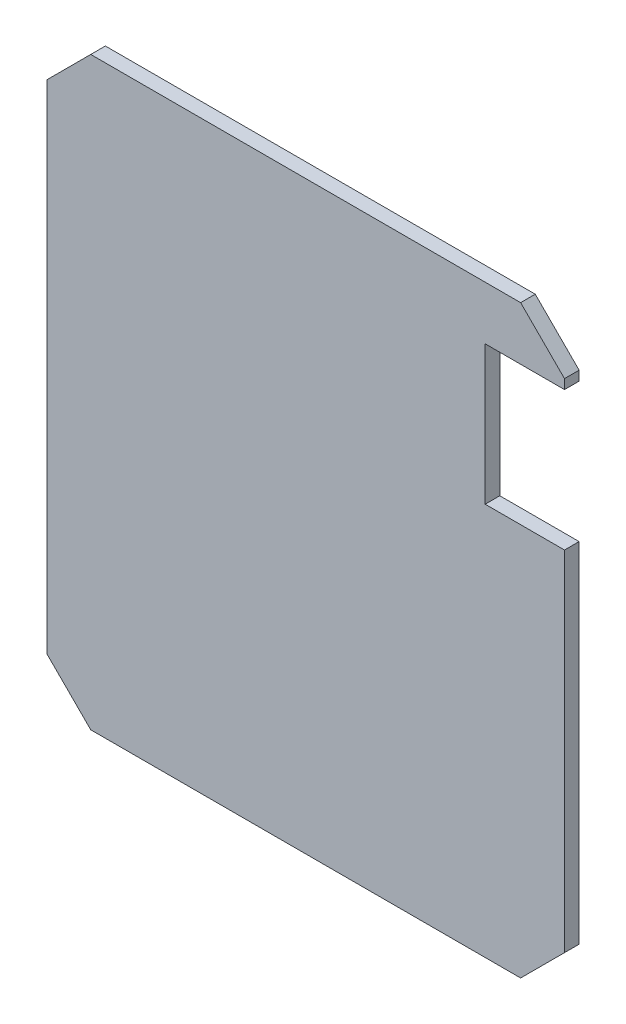
SolidWorks part; units mm, degrees
ref_plane "Front Plane" through (0, 0, 0) normal (0, 0, 1) x (1, 0, 0)
ref_plane "Top Plane" through (0, 0, 0) normal (0, 1, 0) x (1, 0, 0)
ref_plane "Right Plane" through (0, 0, 0) normal (1, 0, 0) x (0, 0, -1)
sketch "Sketch3" plane through (0, 0, 0) normal (0, 0, 1) x (1, 0, 0)
  line L0 (-17.75, 17) -> (-17.75, -17) construction
  line L1 (-14.7, 20) -> (14.7, 20)
  line L2 (-17.7, 17) -> (-17.7, -17)
  line L3 (-14.7, -20) -> (14.7, -20)
  line L4 (17.7, 17) -> (17.7, -17)
  line L5 (-17.7, 20) -> (17.7, -20) construction
  line L6 (-17.7, -20) -> (17.7, 20) construction
  line L7 (-17.7, 17) -> (-14.7, 20)
  line L8 (14.7, 20) -> (17.7, 17)
  line L9 (-17.7, -17) -> (-14.7, -20)
  line L10 (14.7, -20) -> (17.7, -17)
  point P0 (0, 0)
  dimension "D1" = 0.05
  dimension "D2" = 40
extrude "Boss-Extrude1" add sketch "Sketch3" along normal blind 1 contours L2 L9 L3 L10 L4 L8 L1 L7
sketch "Sketch4" plane through (0, 0, 1) normal (0, 0, 1) x (1, 0, 0)
  line L0 (17.7, 17) -> (17.7, -17) construction
  line L1 (17.7, 16.349) -> (12.2747, 16.349)
  line L2 (17.7, 16.349) -> (17.7, 6.849)
  line L3 (17.7, 6.849) -> (12.2747, 6.849)
  line L4 (12.2747, 16.349) -> (12.2747, 6.849)
  line L5 (14.0247, 15.349) -> (13.2747, 15.349) construction
  line L6 (14.0247, 7.849) -> (13.2747, 7.849) construction
  line L7 (13.2747, 8.399) -> (13.2747, 7.849) construction
  dimension "D1" = 1
  dimension "D2" = 1
  dimension "D3" = 1
extrude "Cut-Extrude1" cut sketch "Sketch4" against normal through all
